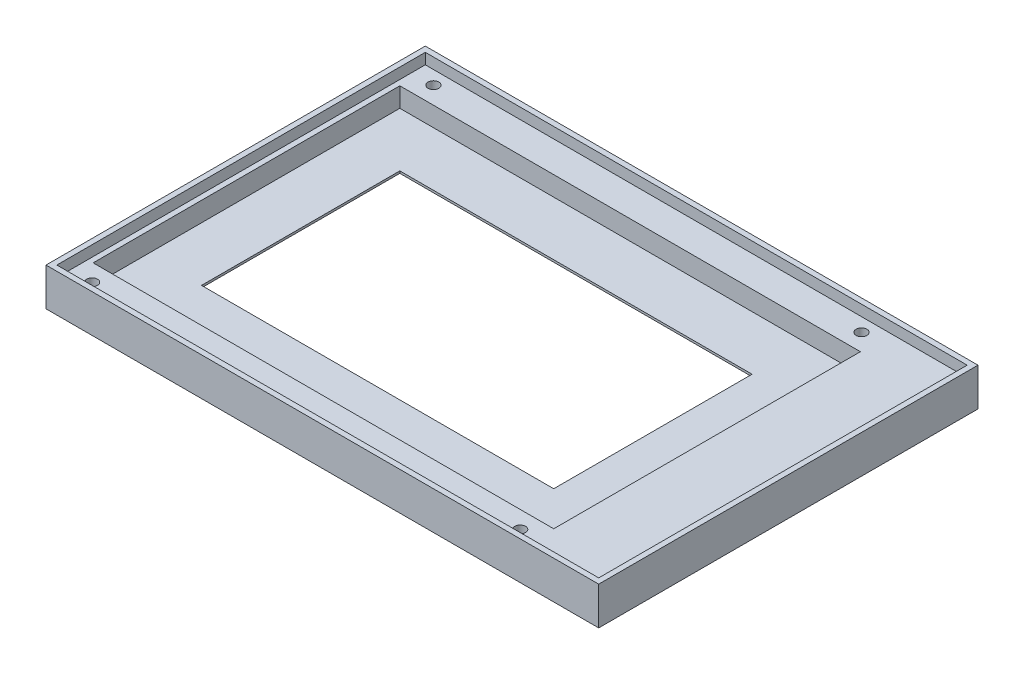
SolidWorks part; units mm, degrees
material "ABS"
ref_plane "Спереди" through (0, 0, 0) normal (0, 0, 1) x (1, 0, 0)
ref_plane "Сверху" through (0, 0, 0) normal (0, 1, 0) x (1, 0, 0)
ref_plane "Справа" through (0, 0, 0) normal (1, 0, 0) x (0, 0, -1)
sketch "Эскиз1" plane through (0, 0, 0) normal (0, 1, 0) x (1, 0, 0)
  line L1 (51, -35) -> (-51, -35)
  line L2 (51, -35) -> (51, 35)
  line L3 (51, 35) -> (-51, 35)
  line L4 (-51, -35) -> (-51, 35)
  line L5 (51, -35) -> (-51, 35) construction
  line L6 (51, 35) -> (-51, -35) construction
  point P0 (0, 0)
extrude "Бобышка-Вытянуть1" add sketch "Эскиз1" along normal blind 5
sketch "Эскиз2" plane through (0, 5, 0) normal (0, 1, 0) x (1, 0, 0)
  line L8 (-49, -28.3) -> (36, -28.3)
  line L9 (-49, -28.3) -> (-49, 28.3)
  line L10 (-49, 28.3) -> (36, 28.3)
  line L11 (36, -28.3) -> (36, 28.3)
extrude "Вырез-Вытянуть1" cut sketch "Эскиз2" against normal blind 3.6
sketch "Эскиз3" plane through (0, 5, 0) normal (0, 1, 0) x (1, 0, 0)
  circle A0 centre (33, -31.5) radius 1
  circle A1 centre (33, 31.5) radius 1
  circle A4 centre (-46, -31.5) radius 1
  circle A5 centre (-46, 31.5) radius 1
extrude "Вырез-Вытянуть2" cut sketch "Эскиз3" against normal blind 6
sketch "Эскиз5" plane through (0, 0, 0) normal (0, -1, 0) x (1, 0, 0)
  line L11 (50, -34) -> (-50, -34)
  line L12 (50, -34) -> (50, 34)
  line L13 (50, 34) -> (-50, 34)
  line L14 (-50, -34) -> (-50, 34)
  point P0 (0, 0)
extrude "Вырез-Вытянуть4" cut sketch "Эскиз5" against normal blind 1
sketch "Эскиз6" plane through (-51, 0, 0) normal (-1, 0, 0) x (0, 0, 1)
  line L1 (-35, 0) -> (35, 0) construction
  line L7 (-3.5, 1) -> (3.5, 1)
  line L8 (-3.5, 1) -> (-3.5, 0)
  line L9 (-3.5, 0) -> (3.5, 0)
  line L10 (3.5, 1) -> (3.5, 0)
extrude "Вырез-Вытянуть5" cut sketch "Эскиз6" against normal blind 1
sketch "Эскиз7" plane through (0, 1.4, 0) normal (0, 1, 0) x (1, 0, 0)
  line L7 (-39, 18.3) -> (26, 18.3)
  line L8 (-39, 18.3) -> (-39, -18.3)
  line L9 (-39, -18.3) -> (26, -18.3)
  line L10 (26, 18.3) -> (26, -18.3)
extrude "Вырез-Вытянуть6" cut sketch "Эскиз7" against normal blind 10
sketch "Эскиз8" plane through (0, 5, 0) normal (0, 1, 0) x (1, 0, 0)
  line L0 (51, -35) -> (51, 35)
  line L1 (-51, 35) -> (51, 35)
  line L2 (-51, 35) -> (-51, -35)
  line L3 (-51, -35) -> (51, -35)
  line L9 (50, -34) -> (-50, -34)
  line L10 (50, -34) -> (50, 34)
  line L11 (50, 34) -> (-50, 34)
  line L12 (-50, -34) -> (-50, 34)
extrude "Бобышка-Вытянуть2" add sketch "Эскиз8" along normal blind 2
